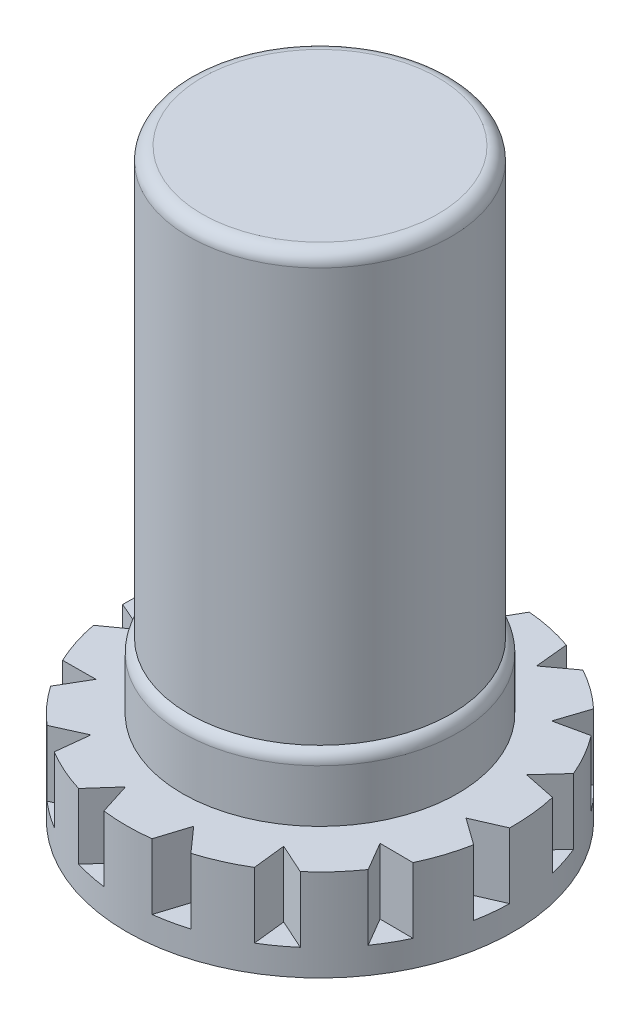
SolidWorks part; units mm, degrees
ref_plane "Plano frontal" through (0, 0, 0) normal (0, 0, 1) x (1, 0, 0)
ref_plane "Plano superior" through (0, 0, 0) normal (0, 1, 0) x (1, 0, 0)
ref_plane "Plano direito" through (0, 0, 0) normal (1, 0, 0) x (0, 0, -1)
sketch "Esboço1" plane through (0, 0, 0) normal (0, 1, 0) x (1, 0, 0)
  circle A0 centre (0, 0) radius 2.95
  dimension "D1" = 5.9
extrude "Ressalto-extrusão1" add sketch "Esboço1" along normal blind 1.4
sketch "Esboço2" plane through (0, 1.4, 0) normal (0, 1, 0) x (1, 0, 0)
  line L0 (-0.25, 2.9394) -> (0, 2.5)
  line L1 (0, 2.5) -> (0.25, 2.9394)
  line L2 (0, 2.95) -> (0, 0) construction
  line L3 (1.0168, 2.2839) -> (1.4239, 2.5836)
  line L4 (0.9672, 2.7869) -> (1.0168, 2.2839)
  line L5 (1.8579, 1.6728) -> (2.3517, 1.781)
  line L6 (2.0171, 2.1526) -> (1.8579, 1.6728)
  line L7 (2.3776, 0.7725) -> (2.8728, 0.6706)
  line L8 (2.7183, 1.1461) -> (2.3776, 0.7725)
  line L9 (2.4863, -0.2613) -> (2.8972, -0.5559)
  line L10 (2.9494, -0.0586) -> (2.4863, -0.2613)
  line L11 (2.1651, -1.25) -> (2.4206, -1.6862)
  line L12 (2.6706, -1.2532) -> (2.1651, -1.25)
  line L13 (1.4695, -2.0225) -> (1.5255, -2.525)
  line L14 (1.93, -2.2311) -> (1.4695, -2.0225)
  line L15 (0.5198, -2.4454) -> (0.3666, -2.9271)
  line L16 (0.8557, -2.8232) -> (0.5198, -2.4454)
  line L17 (-0.5198, -2.4454) -> (-0.8557, -2.8232)
  line L18 (-0.3666, -2.9271) -> (-0.5198, -2.4454)
  line L19 (-1.4695, -2.0225) -> (-1.93, -2.2311)
  line L20 (-1.5255, -2.525) -> (-1.4695, -2.0225)
  line L21 (-2.1651, -1.25) -> (-2.6706, -1.2532)
  line L22 (-2.4206, -1.6862) -> (-2.1651, -1.25)
  line L23 (-2.4863, -0.2613) -> (-2.9494, -0.0586)
  line L24 (-2.8972, -0.5559) -> (-2.4863, -0.2613)
  line L25 (-2.3776, 0.7725) -> (-2.7183, 1.1461)
  line L26 (-2.8728, 0.6706) -> (-2.3776, 0.7725)
  line L27 (-1.8579, 1.6728) -> (-2.0171, 2.1526)
  line L28 (-2.3517, 1.781) -> (-1.8579, 1.6728)
  line L29 (-1.0168, 2.2839) -> (-0.9672, 2.7869)
  line L30 (-1.4239, 2.5836) -> (-1.0168, 2.2839)
  circle A0 centre (0, 0) radius 2.95 construction
  arc A1 (0.25, 2.9394) -> (-0.25, 2.9394) centre (0, 0) ccw
  arc A2 (1.4239, 2.5836) -> (0.9672, 2.7869) centre (0, 0) ccw
  arc A3 (2.3517, 1.781) -> (2.0171, 2.1526) centre (0, 0) ccw
  arc A4 (2.8728, 0.6706) -> (2.7183, 1.1461) centre (0, 0) ccw
  arc A5 (2.8972, -0.5559) -> (2.9494, -0.0586) centre (0, 0) ccw
  arc A6 (2.4206, -1.6862) -> (2.6706, -1.2532) centre (0, 0) ccw
  arc A7 (1.5255, -2.525) -> (1.93, -2.2311) centre (0, 0) ccw
  arc A8 (0.3666, -2.9271) -> (0.8557, -2.8232) centre (0, 0) ccw
  arc A9 (-0.8557, -2.8232) -> (-0.3666, -2.9271) centre (0, 0) ccw
  arc A10 (-1.93, -2.2311) -> (-1.5255, -2.525) centre (0, 0) ccw
  arc A11 (-2.6706, -1.2532) -> (-2.4206, -1.6862) centre (0, 0) ccw
  arc A12 (-2.9494, -0.0586) -> (-2.8972, -0.5559) centre (0, 0) ccw
  arc A13 (-2.7183, 1.1461) -> (-2.8728, 0.6706) centre (0, 0) ccw
  arc A14 (-2.0171, 2.1526) -> (-2.3517, 1.781) centre (0, 0) ccw
  arc A15 (-0.9672, 2.7869) -> (-1.4239, 2.5836) centre (0, 0) ccw
  point P52 (0, 0)
  dimension "D1" = 2.5
  dimension "D2" = 0.25
  dimension "D3" = 0.25
  dimension "D4" = 15
extrude "Corte-extrusão1" cut sketch "Esboço2" against normal blind 1
sketch "Esboço3" plane through (0, 1.4, 0) normal (0, 1, 0) x (1, 0, 0)
  circle A0 centre (0, 0) radius 2.1
  dimension "D1" = 4.2
extrude "Ressalto-extrusão2" add sketch "Esboço3" along normal blind 1
fillet "Filete3" radius 0.2 1 edges at (0, 2.4, 2.1)
sketch "Esboço4" plane through (0, 2.4, 0) normal (0, 1, 0) x (1, 0, 0)
  circle A0 centre (0, 0) radius 2
  dimension "D1" = 4
extrude "Ressalto-extrusão3" add sketch "Esboço4" along normal blind 6.5
fillet "Filete4" radius 0.2 1 edges at (0, 8.9, 2)
